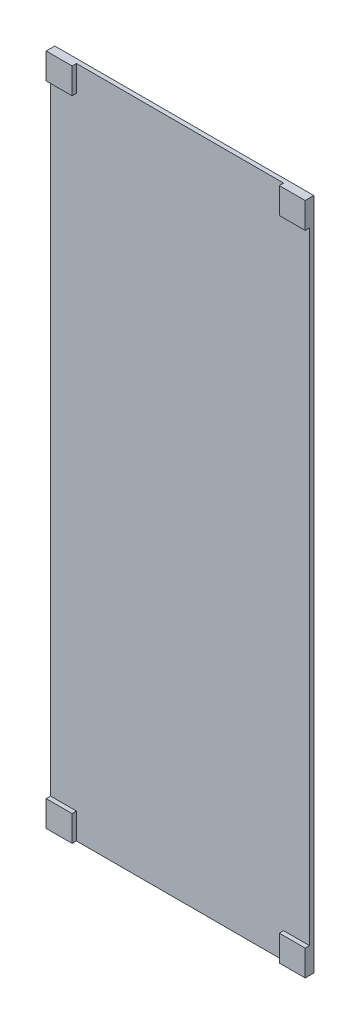
SolidWorks part; units mm, degrees
ref_plane "Front Plane" through (0, 0, 0) normal (0, 0, 1) x (1, 0, 0)
ref_plane "Top Plane" through (0, 0, 0) normal (0, 1, 0) x (1, 0, 0)
ref_plane "Right Plane" through (0, 0, 0) normal (1, 0, 0) x (0, 0, -1)
sketch "Sketch1" plane through (0, 0, 0) normal (0, 0, 1) x (1, 0, 0)
  line L1 (0, 0) -> (1524, 0)
  line L2 (0, 0) -> (0, 3962.4)
  line L3 (0, 3962.4) -> (1524, 3962.4)
  line L4 (1524, 0) -> (1524, 3962.4)
  dimension "D1" = 3962.4
  dimension "D2" = 1524
extrude "Boss-Extrude1" add sketch "Sketch1" along normal blind 25.4
sketch "Sketch2" plane through (0, 0, 25.4) normal (0, 0, 1) x (1, 0, 0)
  line L0 (0, 1981.2) -> (1524, 1981.2) construction
  line L1 (0, 3962.4) -> (152.4, 3962.4)
  line L2 (0, 3962.4) -> (0, 3810)
  line L3 (0, 3810) -> (152.4, 3810)
  line L4 (152.4, 3962.4) -> (152.4, 3810)
  line L5 (1524, 3962.4) -> (1371.6, 3962.4)
  line L6 (1524, 3962.4) -> (1524, 3810)
  line L7 (1524, 3810) -> (1371.6, 3810)
  line L8 (1371.6, 3962.4) -> (1371.6, 3810)
  line L9 (0, 3962.4) -> (0, 0) construction
  line L10 (1524, 0) -> (1524, 3962.4) construction
  line L11 (1524, 152.4) -> (1371.6, 152.4)
  line L12 (1371.6, 0) -> (1371.6, 152.4)
  line L13 (1524, 0) -> (1371.6, 0)
  line L14 (1524, 0) -> (1524, 152.4)
  line L15 (0, 152.4) -> (152.4, 152.4)
  line L16 (152.4, 0) -> (152.4, 152.4)
  line L17 (0, 0) -> (152.4, 0)
  line L18 (0, 0) -> (0, 152.4)
  dimension "D1" = 152.4
  dimension "D2" = 152.4
  dimension "D3" = 152.4
  dimension "D4" = 152.4
extrude "Boss-Extrude2" add sketch "Sketch2" along normal blind 25.4
